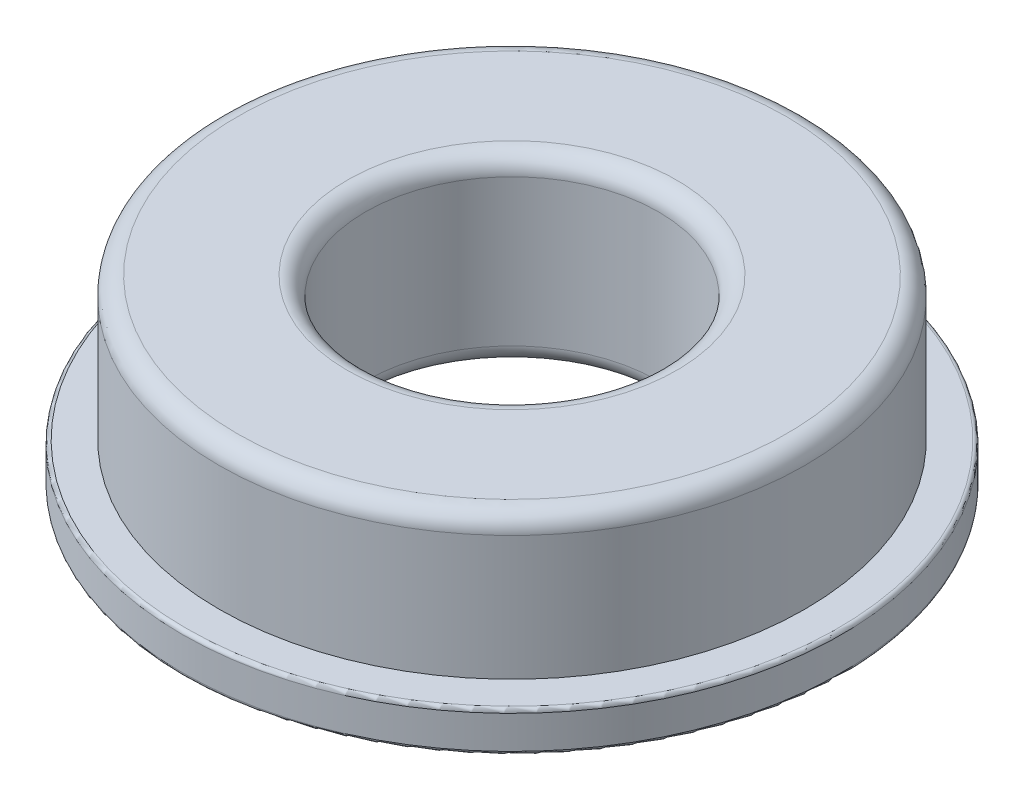
SolidWorks part; units mm, degrees
ref_plane "Front Plane" through (0, 0, 0) normal (0, 0, 1) x (1, 0, 0)
ref_plane "Top Plane" through (0, 0, 0) normal (0, 1, 0) x (1, 0, 0)
ref_plane "Right Plane" through (0, 0, 0) normal (1, 0, 0) x (0, 0, -1)
sketch "Sketch1" plane through (0, 0, 0) normal (0, 1, 0) x (1, 0, 0)
  circle A0 centre (0, 0) radius 9
  dimension "D1" = 18
extrude "Boss-Extrude1" add sketch "Sketch1" along normal blind 5
sketch "Sketch2" plane through (0, 5, 0) normal (0, 1, 0) x (1, 0, 0)
  circle A0 centre (0, 0) radius 9
  circle A1 centre (0, 0) radius 8
  dimension "D1" = 18
  dimension "D2" = 16
extrude "Cut-Extrude1" cut sketch "Sketch2" against normal blind 3.9
sketch "Sketch3" plane through (0, 5, 0) normal (0, 1, 0) x (1, 0, 0)
  circle A0 centre (0, 0) radius 4
  dimension "D1" = 8
extrude "Cut-Extrude2" cut sketch "Sketch3" against normal blind 5
fillet "Fillet1" radius 0.5 3 edges at (0, 0, 4) (0, 5, 4) (0, 5, 8)
fillet "Fillet2" radius 0.1 1 edges at (0, 1.1, 9)
fillet "Fillet3" radius 0.1 1 edges at (0, 0, 9)
